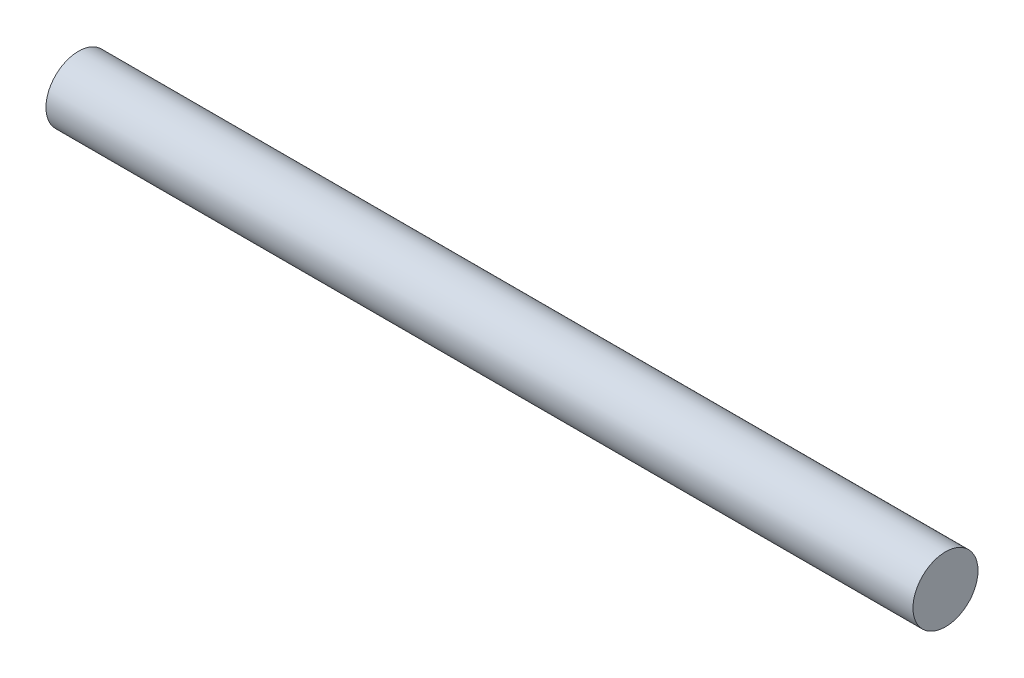
SolidWorks part; units mm, degrees
ref_plane "Front Plane" through (0, 0, 0) normal (0, 0, 1) x (1, 0, 0)
ref_plane "Top Plane" through (0, 0, 0) normal (0, 1, 0) x (1, 0, 0)
ref_plane "Right Plane" through (0, 0, 0) normal (1, 0, 0) x (0, 0, -1)
sketch "Sketch1" plane through (0, 0, 0) normal (1, 0, 0) x (0, 0, -1)
  circle A0 centre (0, 0) radius 0.6
  dimension "D1" = 1.2
extrude "Boss-Extrude1" add sketch "Sketch1" along normal blind 16
